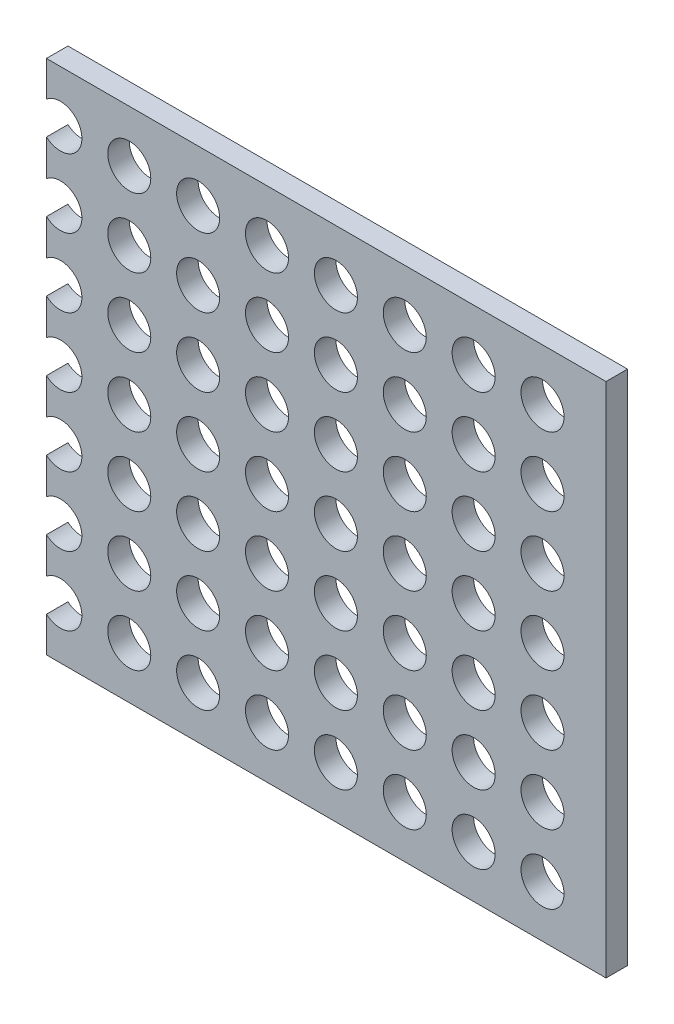
SolidWorks part; units mm, degrees
material "6061-T6 (SS)"
ref_plane "Front Plane" through (0, 0, 0) normal (0, 0, 1) x (1, 0, 0)
ref_plane "Top Plane" through (0, 0, 0) normal (0, 1, 0) x (1, 0, 0)
ref_plane "Right Plane" through (0, 0, 0) normal (1, 0, 0) x (0, 0, -1)
sketch "Sketch1" plane through (0, 0, 0) normal (0, 0, 1) x (1, 0, 0)
  line L1 (-41.275, -38.1) -> (41.275, -38.1)
  line L2 (-41.275, -38.1) -> (-41.275, 38.1)
  line L3 (-41.275, 38.1) -> (41.275, 38.1)
  line L4 (41.275, -38.1) -> (41.275, 38.1)
  line L5 (-41.275, -38.1) -> (41.275, 38.1) construction
  line L6 (-41.275, 38.1) -> (41.275, -38.1) construction
  point P0 (0, 0)
  dimension "D1" = 82.55
  dimension "D2" = 76.2
extrude "Boss-Extrude1" add sketch "Sketch1" along normal blind 3.175
sketch "Sketch2" plane through (0, 0, 3.175) normal (0, 0, 1) x (1, 0, 0)
  line L0 (0, 0) -> (-8.7376, 0) construction
  dimension "D1" = 8.7376
hole_wizard "1/4 (0.25) Diameter Hole1" positions "Sketch4" profile "Sketch3" hole size "1/4" standard "Ansi Inch"
sketch "Sketch4" plane through (0, 0, 3.175) normal (0, 0, 1) x (1, 0, 0)
  point P14 (-8.7376, 0)
sketch "Sketch3" plane through (-8.7376, 0, 3.175) normal (1, 0, 0) x (0, -1, 0)
  line L0 (0, 0) -> (0, 17.1477)
  line L1 (0, 17.1477) -> (3.175, 15.24)
  line L2 (3.175, 15.24) -> (3.175, 0)
  line L5 (3.175, 0) -> (0, 0)
  line L10 (0, 17.1477) -> (-3.175, 15.24) construction
  line L11 (0, -6.35) -> (0, 107.95) construction
  dimension "Hole Dia." = 6.35
  dimension "Hole Depth" = 15.24
  dimension "Drill Angle" = 118
pattern_linear "LPattern1" count 5 spacing 10.16 along (1, 0, 0) count 4 spacing 10.16 along (-1, 0, 0) of "1/4 (0.25) Diameter Hole1"
pattern_linear "LPattern2" count 4 spacing 10.16 along (0, -1, 0) count 4 spacing 10.16 along (0, 1, 0) of "LPattern1", "1/4 (0.25) Diameter Hole1"
